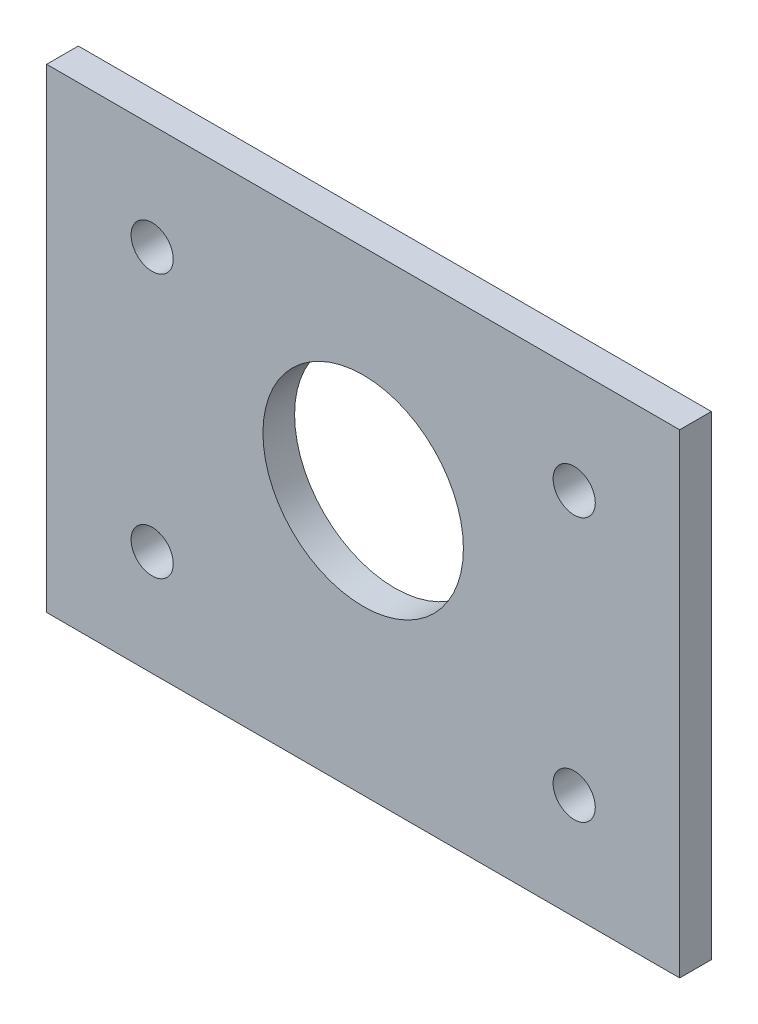
SolidWorks part; units mm, degrees
ref_plane "前视基准面" through (0, 0, 0) normal (0, 0, 1) x (1, 0, 0)
ref_plane "上视基准面" through (0, 0, 0) normal (0, 1, 0) x (1, 0, 0)
ref_plane "右视基准面" through (0, 0, 0) normal (1, 0, 0) x (0, 0, -1)
other "Configuration Table"
sketch "草图1" plane through (0, 0, 0) normal (0, 0, 1) x (1, 0, 0)
  line L0 (-1000, 0) -> (49000, 0) construction
  line L1 (-30, -22.5) -> (30, -22.5)
  line L2 (-30, -22.5) -> (-30, 22.5)
  line L3 (-30, 22.5) -> (30, 22.5)
  line L4 (30, -22.5) -> (30, 22.5)
  line L5 (-30, -22.5) -> (30, 22.5) construction
  line L6 (-30, 22.5) -> (30, -22.5) construction
  line L7 (-30, 22.5) -> (-20, 22.5)
  line L8 (-30, 22.5) -> (-30, 12.5)
  line L9 (-30, 12.5) -> (-20, 12.5)
  line L10 (-20, 22.5) -> (-20, 12.5)
  line L11 (0, -1000) -> (0, 49000) construction
  circle A0 centre (-20, 12.5) radius 2
  circle A1 centre (20, 12.5) radius 2
  circle A2 centre (20, -12.5) radius 2
  circle A3 centre (-20, -12.5) radius 2
  circle A5 centre (0, 2.5) radius 9.5
  point P0 (0, 0)
  dimension "D5" = 4
  dimension "D6" = 25
  dimension "D7" = 19
  dimension "D1" = 45
  dimension "D2" = 60
  dimension "D3" = 10
  dimension "D4" = 10
extrude "凸台-拉伸2" add sketch "草图1" along normal mid plane 3 contours A0 L9 L2 L1 L4 L3 L10 A5 A1 A2 A3 | A0 L10 L3 L2 L9
